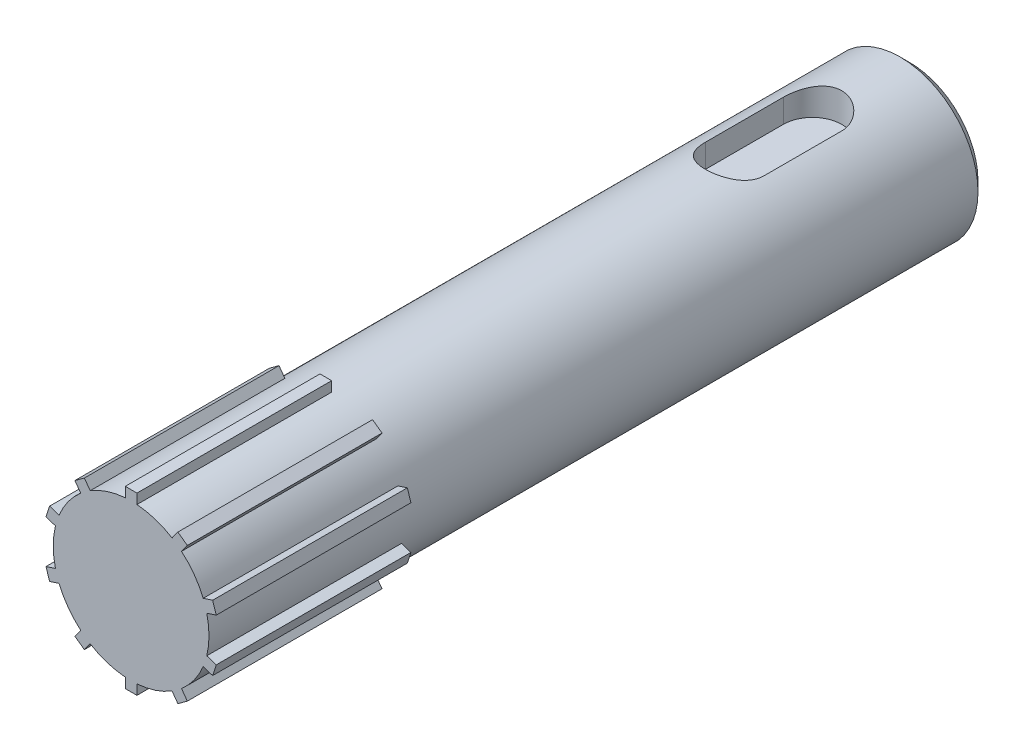
SolidWorks part; units mm, degrees
ref_plane "Front Plane" through (0, 0, 0) normal (0, 0, 1) x (1, 0, 0)
ref_plane "Top Plane" through (0, 0, 0) normal (0, 1, 0) x (1, 0, 0)
ref_plane "Right Plane" through (0, 0, 0) normal (1, 0, 0) x (0, 0, -1)
sketch "Sketch1" plane through (0, 0, 0) normal (0, 0, 1) x (1, 0, 0)
  circle A0 centre (0, 0) radius 4
  dimension "D1" = 8
extrude "Boss-Extrude1" add sketch "Sketch1" along normal blind 40
sketch "Sketch2" plane through (0, 0, 0) normal (0, 1, 0) x (1, 0, 0)
  line L0 (0, 0) -> (0, -17.5016) construction
  line L1 (0, -9) -> (0, -5) construction
  line L2 (-1.5, -9) -> (-1.5, -5)
  line L3 (1.5, -9) -> (1.5, -5)
  arc A0 (-1.5, -9) -> (1.5, -9) centre (0, -9) ccw
  arc A1 (1.5, -5) -> (-1.5, -5) centre (0, -5) ccw
  point P5 (0, -7)
  dimension "D3" = 1.5
  dimension "D1" = 5
  dimension "D2" = 4
extrude "Cut-Extrude1" cut sketch "Sketch2" along normal through all from offset 2.5
sketch "Sketch3" plane through (0, 0, 40) normal (0, 0, 1) x (1, 0, 0)
  line L0 (0, 0) -> (0, 4) construction
  line L2 (-0.3, 2) -> (0.3, 2)
  line L3 (-0.3, 2) -> (-0.3, 4.5)
  line L4 (-0.3, 4.5) -> (0.3, 4.5)
  line L5 (0.3, 2) -> (0.3, 4.5)
  circle A0 centre (0, 0) radius 4 construction
  point P10 (0, 2)
  dimension "D1" = 0.6
  dimension "D2" = 4.5
extrude "Boss-Extrude2" add sketch "Sketch3" against normal blind 10
pattern_circular "CirPattern1" count 10 over 360 about axis through (0, 0, 0) along (0, 0, 1) of "Boss-Extrude2"
chamfer "Chamfer1" distance 0.5 angle 45 1 edges at (4, 0, 0)
